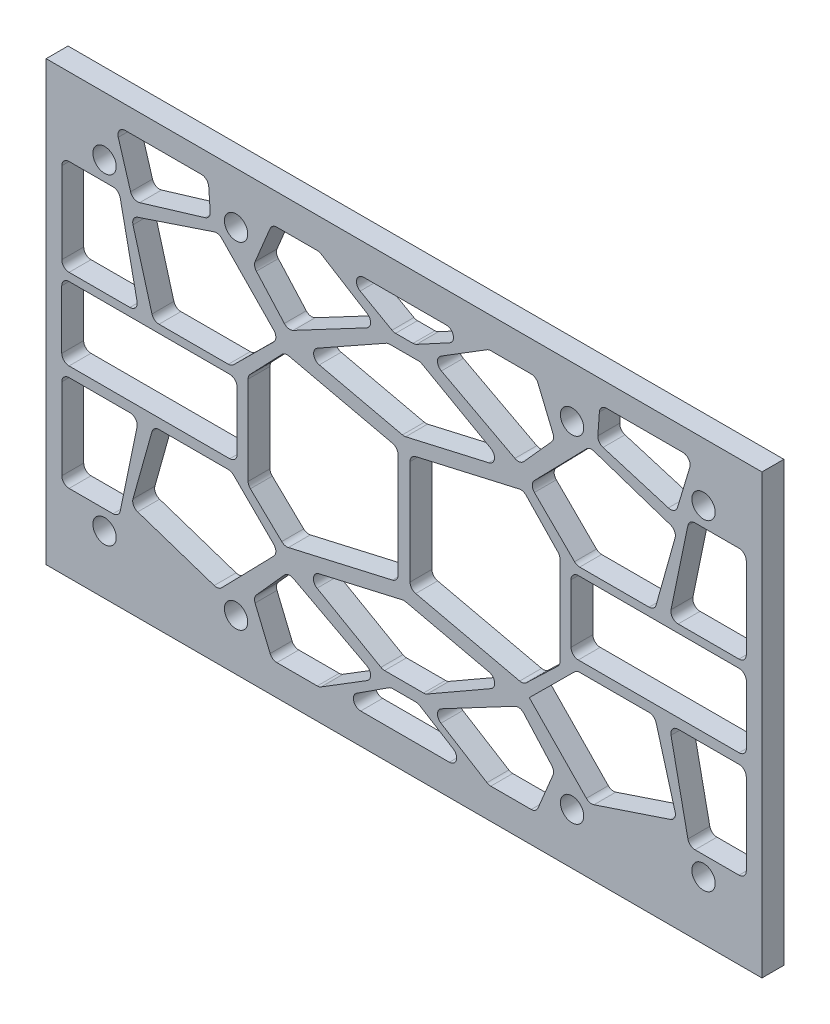
SolidWorks part; units mm, degrees
material "Thornel Mat VMA"
ref_plane "前视基准面" through (0, 0, 0) normal (0, 0, 1) x (1, 0, 0)
ref_plane "上视基准面" through (0, 0, 0) normal (0, 1, 0) x (1, 0, 0)
ref_plane "右视基准面" through (0, 0, 0) normal (1, 0, 0) x (0, 0, -1)
other "Configuration Table"
sketch "草图1" plane through (0, 0, 0) normal (0, 0, 1) x (1, 0, 0)
  line L0 (49, 0) -> (49, 79.4634) construction
  line L1 (0, 0) -> (98, 0)
  line L2 (0, 0) -> (0, 60)
  line L3 (0, 60) -> (98, 60)
  line L4 (98, 0) -> (98, 60)
  line L5 (0, 30) -> (168.6186, 30) construction
  line L7 (34.8707, 42.966) -> (49, 39.7317)
  line L8 (49, 39.7317) -> (63.1293, 42.966)
  line L9 (63.1293, 42.966) -> (51.2305, 49.6584)
  line L10 (49.8207, 37.9395) -> (65.3258, 41.4888)
  line L11 (65.3258, 41.4888) -> (70.347, 36.2413)
  line L12 (70.347, 36.2413) -> (70.347, 23.2804)
  line L13 (70.347, 23.2804) -> (65.3557, 18.5044)
  line L14 (65.3557, 18.5044) -> (49.8207, 22.0605)
  line L15 (49.8207, 22.0605) -> (49.8207, 37.9395)
  line L40 (49, 20.2683) -> (63.1293, 17.034)
  line L41 (34.8707, 17.034) -> (49, 20.2683)
  line L42 (46.0661, 10.6206) -> (34.8707, 17.034)
  line L43 (63.1293, 17.034) -> (51.9339, 10.6206)
  line L65 (33.1347, 44.3303) -> (28.3657, 49.6584)
  line L66 (45.4305, 50.843) -> (33.1347, 44.3303)
  line L67 (37.4062, 55.8127) -> (45.4305, 50.843)
  line L68 (32.6443, 18.5044) -> (48.1793, 22.0605)
  line L69 (27.653, 23.2804) -> (32.6443, 18.5044)
  line L70 (27.653, 36.2413) -> (27.653, 23.2804)
  line L71 (32.6742, 41.4888) -> (27.653, 36.2413)
  line L72 (48.1793, 37.9395) -> (32.6742, 41.4888)
  line L73 (48.1793, 22.0605) -> (48.1793, 37.9395)
  line L74 (28.3657, 49.6584) -> (30.923, 55.8127)
  line L75 (30.923, 55.8127) -> (37.4062, 55.8127)
  line L76 (52.5695, 50.843) -> (64.8653, 44.3303)
  line L77 (60.5938, 55.8127) -> (52.5695, 50.843)
  line L78 (67.077, 55.8127) -> (60.5938, 55.8127)
  line L79 (69.6343, 49.6584) -> (67.077, 55.8127)
  line L81 (64.8653, 44.3303) -> (69.6343, 49.6584)
  line L82 (60.5938, 4.1873) -> (52.5695, 9.157)
  line L83 (67.077, 4.1873) -> (60.5938, 4.1873)
  line L84 (69.6343, 10.3416) -> (67.077, 4.1873)
  line L85 (64.8653, 15.6697) -> (69.6343, 10.3416)
  line L86 (52.5695, 9.157) -> (64.8653, 15.6697)
  line L87 (45.4305, 9.157) -> (33.1347, 15.6697)
  line L88 (37.4062, 4.1873) -> (45.4305, 9.157)
  line L89 (30.923, 4.1873) -> (37.4062, 4.1873)
  line L90 (28.3657, 10.3416) -> (30.923, 4.1873)
  line L91 (33.1347, 15.6697) -> (28.3657, 10.3416)
  line L92 (47.173, 9.0299) -> (39.6695, 4.1873)
  line L93 (39.6695, 4.1873) -> (58.723, 4.1873)
  line L94 (58.723, 4.1873) -> (50.9039, 9.0299)
  line L95 (39.6695, 55.8127) -> (58.723, 55.8127)
  line L96 (47.5795, 51.3572) -> (39.6695, 55.8127)
  line L97 (58.723, 55.8127) -> (50.4802, 51.3572)
  line L98 (66.1436, 42.6867) -> (74.3992, 51.1631)
  line L99 (74.3992, 51.1631) -> (86.3678, 47.1642)
  line L100 (86.3678, 47.1642) -> (83.3052, 36.2413)
  line L101 (83.3052, 36.2413) -> (72.6368, 36.2413)
  line L102 (72.6368, 36.2413) -> (66.1436, 42.6867)
  line L103 (14.6948, 36.2413) -> (25.3632, 36.2413)
  line L104 (71.8577, 35.1475) -> (95.8629, 35.1475)
  line L105 (71.8577, 35.1475) -> (71.8577, 25.1355)
  line L106 (71.8577, 25.1355) -> (95.8629, 25.1355)
  line L107 (95.8629, 35.1475) -> (95.8629, 25.1355)
  line L108 (11.6322, 47.1642) -> (14.6948, 36.2413)
  line L109 (23.6008, 51.1631) -> (11.6322, 47.1642)
  line L110 (31.8564, 42.6867) -> (23.6008, 51.1631)
  line L111 (25.3632, 36.2413) -> (31.8564, 42.6867)
  line L112 (83.3052, 23.7587) -> (72.6368, 23.7587)
  line L113 (86.3678, 12.8358) -> (83.3052, 23.7587)
  line L114 (74.3992, 8.8369) -> (86.3678, 12.8358)
  line L115 (66.1436, 17.3133) -> (74.3992, 8.8369)
  line L116 (72.6368, 23.7587) -> (66.1436, 17.3133)
  line L117 (11.6322, 12.8358) -> (14.6948, 23.7587)
  line L118 (23.6008, 8.8369) -> (11.6322, 12.8358)
  line L119 (31.8564, 17.3133) -> (23.6008, 8.8369)
  line L120 (25.3632, 23.7587) -> (31.8564, 17.3133)
  line L121 (14.6948, 23.7587) -> (25.3632, 23.7587)
  line L122 (26.1423, 25.1355) -> (2.1371, 25.1355)
  line L123 (2.1371, 35.1475) -> (2.1371, 25.1355)
  line L124 (26.1423, 35.1475) -> (2.1371, 35.1475)
  line L125 (26.1423, 35.1475) -> (26.1423, 25.1355)
  line L126 (85.2991, 36.2413) -> (88.0272, 49.3794)
  line L127 (88.0272, 49.3794) -> (95.8539, 49.3794)
  line L128 (95.8539, 49.3794) -> (95.8539, 36.2413)
  line L129 (95.8539, 36.2413) -> (85.2991, 36.2413)
  line L130 (2.1461, 49.3794) -> (2.1461, 36.2413)
  line L131 (9.9728, 49.3794) -> (2.1461, 49.3794)
  line L132 (12.7009, 36.2413) -> (9.9728, 49.3794)
  line L133 (2.1461, 36.2413) -> (12.7009, 36.2413)
  line L134 (95.8539, 10.6206) -> (95.8539, 23.7587)
  line L135 (88.0272, 10.6206) -> (95.8539, 10.6206)
  line L136 (85.2991, 23.7587) -> (88.0272, 10.6206)
  line L137 (95.8539, 23.7587) -> (85.2991, 23.7587)
  line L138 (9.9728, 10.6206) -> (2.1461, 10.6206)
  line L139 (12.7009, 23.7587) -> (9.9728, 10.6206)
  line L140 (2.1461, 23.7587) -> (12.7009, 23.7587)
  line L141 (2.1461, 10.6206) -> (2.1461, 23.7587)
  line L142 (75.8055, 56.9042) -> (75.4791, 52.2563)
  line L143 (75.4791, 52.2563) -> (86.1483, 49.0438)
  line L144 (86.1483, 49.0438) -> (88.5151, 56.9042)
  line L145 (88.5151, 56.9042) -> (75.8055, 56.9042)
  line L146 (11.8517, 49.0438) -> (9.4849, 56.9042)
  line L147 (22.5209, 52.2563) -> (11.8517, 49.0438)
  line L148 (22.1945, 56.9042) -> (22.5209, 52.2563)
  line L149 (9.4849, 56.9042) -> (22.1945, 56.9042)
  line L150 (46.0661, 10.6206) -> (51.9339, 10.6206)
  line L151 (46.7695, 49.6584) -> (51.2305, 49.6584)
  line L152 (47.5795, 51.3572) -> (50.4802, 51.3572)
  line L153 (46.7695, 49.6584) -> (34.8707, 42.966)
  line L154 (47.173, 9.0299) -> (50.9039, 9.0299)
  circle A0 centre (8, 8) radius 1.6
  circle A1 centre (90, 8) radius 1.6
  circle A2 centre (90, 52) radius 1.6
  circle A3 centre (8, 52) radius 1.6
  circle A4 centre (26, 53) radius 1.6
  circle A5 centre (26, 7) radius 1.6
  circle A8 centre (72, 7) radius 1.6
  circle A11 centre (72, 53) radius 1.6
  dimension "D4" = 3.2
  dimension "D10" = 3.2
  dimension "D1" = 98
  dimension "D2" = 60
  dimension "D3" = 8
  dimension "D5" = 8
  dimension "D6" = 46
  dimension "D7" = 46
extrude "凸台-拉伸1" add sketch "草图1" along normal blind 3
fillet "圆角1" radius 1 78 edges at (71.8577, 35.1475, 1.5) (49.8207, 22.0605, 1.5) (65.3557, 18.5044, 1.5) (70.347, 23.2804, 1.5) (70.347, 36.2413, 1.5) (65.3258, 41.4888, 1.5) (45.4305, 50.843, 1.5) (49, 39.7317, 1.5) (63.1293, 42.966, 1.5) (49, 20.2683, 1.5) (34.8707, 17.034, 1.5) (63.1293, 17.034, 1.5) (27.653, 36.2413, 1.5) (27.653, 23.2804, 1.5) (32.6443, 18.5044, 1.5) (48.1793, 22.0605, 1.5) (32.6742, 41.4888, 1.5) (30.923, 4.1873, 1.5) (28.3657, 10.3416, 1.5) (45.4305, 9.157, 1.5) (58.723, 4.1873, 1.5) (52.5695, 9.157, 1.5) (67.077, 4.1873, 1.5) (69.6343, 10.3416, 1.5) (67.077, 55.8127, 1.5) (60.5938, 55.8127, 1.5) (52.5695, 50.843, 1.5) (28.3657, 49.6584, 1.5) (37.4062, 55.8127, 1.5) (39.6695, 55.8127, 1.5) (58.723, 55.8127, 1.5) (86.3678, 47.1642, 1.5) (66.1436, 42.6867, 1.5) (74.3992, 51.1631, 1.5) (88.0272, 49.3794, 1.5) (85.2991, 36.2413, 1.5) (85.2991, 23.7587, 1.5) (72.6368, 23.7587, 1.5) (95.8629, 25.1355, 1.5) (71.8577, 25.1355, 1.5) (9.9728, 10.6206, 1.5) (31.8564, 17.3133, 1.5) (25.3632, 23.7587, 1.5) (2.1461, 36.2413, 1.5) (12.7009, 36.2413, 1.5) (9.9728, 49.3794, 1.5) (2.1461, 49.3794, 1.5) (2.1461, 10.6206, 1.5) (11.6322, 12.8358, 1.5) (74.3992, 8.8369, 1.5) (86.3678, 12.8358, 1.5) (88.0272, 10.6206, 1.5) (95.8539, 23.7587, 1.5) (95.8539, 10.6206, 1.5) (12.7009, 23.7587, 1.5) (2.1371, 35.1475, 1.5) (2.1371, 25.1355, 1.5) (26.1423, 25.1355, 1.5) (26.1423, 35.1475, 1.5) (23.6008, 51.1631, 1.5) (31.8564, 42.6867, 1.5) (25.3632, 36.2413, 1.5) (14.6948, 36.2413, 1.5) (88.5151, 56.9042, 1.5) (86.1483, 49.0438, 1.5) (75.4791, 52.2563, 1.5) (75.8055, 56.9042, 1.5) (9.4849, 56.9042, 1.5) (11.8517, 49.0438, 1.5) (22.1945, 56.9042, 1.5) (22.5209, 52.2563, 1.5) (51.9339, 10.6206, 1.5) (34.8707, 42.966, 1.5) (46.7695, 49.6584, 1.5) (51.2305, 49.6584, 1.5) (50.4802, 51.3572, 1.5) (47.173, 9.0299, 1.5) (50.9039, 9.0299, 1.5)
